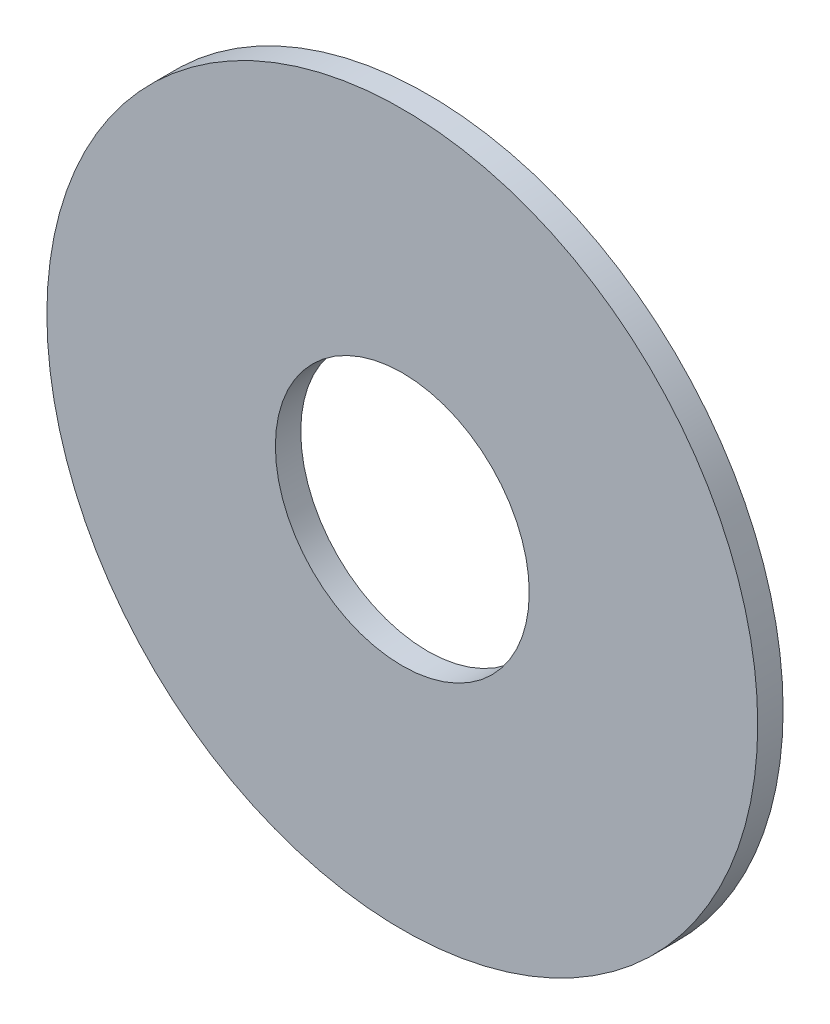
SolidWorks part; units mm, degrees
ref_plane "前视基准面" through (0, 0, 0) normal (0, 0, 1) x (1, 0, 0)
ref_plane "上视基准面" through (0, 0, 0) normal (0, 1, 0) x (1, 0, 0)
ref_plane "右视基准面" through (0, 0, 0) normal (1, 0, 0) x (0, 0, -1)
sketch "草图1" plane through (0, 0, 0) normal (0, 0, 1) x (1, 0, 0)
  circle A0 centre (0, 0) radius 140
  circle A1 centre (0, 0) radius 50
  dimension "D1" = 280
  dimension "D2" = 100
extrude "凸台-拉伸1" add sketch "草图1" along normal blind 10
